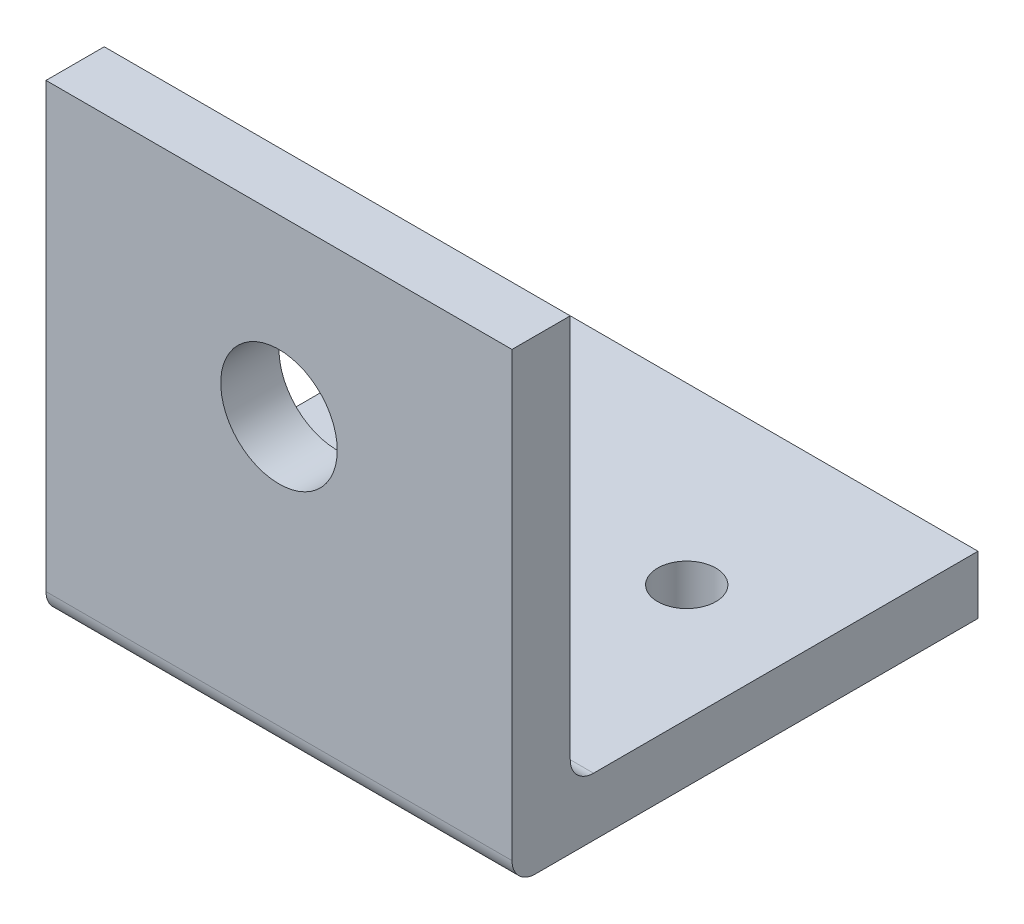
SolidWorks part; units mm, degrees
ref_plane "Ön Düzlem" through (0, 0, 0) normal (0, 0, 1) x (1, 0, 0)
ref_plane "Üst Düzlem" through (0, 0, 0) normal (0, 1, 0) x (1, 0, 0)
ref_plane "Sağ Düzlem" through (0, 0, 0) normal (1, 0, 0) x (0, 0, -1)
sketch "Çizim1" plane through (0, 0, 0) normal (1, 0, 0) x (0, 0, -1)
  line L0 (-17.8957, 38.6433) -> (-17.8957, 0.6433)
  line L1 (-15.8957, -1.3567) -> (22.1043, -1.3567)
  line L2 (-12.8957, 38.6433) -> (-12.8957, 3.6433)
  line L3 (-12.8957, 3.6433) -> (22.1043, 3.6433)
  line L4 (-17.8957, 38.6433) -> (-12.8957, 38.6433)
  line L5 (22.1043, -1.3567) -> (22.1043, 3.6433)
  arc A0 (-17.8957, 0.6433) -> (-15.8957, -1.3567) centre (-15.8957, 0.6433) ccw
  arc A1 (-12.8957, 3.6433) -> (-12.8957, 3.6433) centre (-12.8957, 3.6433) ccw
  dimension "D1" = 2
  dimension "D2" = 38
  dimension "D3" = 38
  dimension "D4" = 5
extrude "Yükseklik-Ekstrüzyon1" add sketch "Çizim1" along normal blind 40
fillet "Radyus1" radius 2 1 edges at (20, 3.6433, 12.8957)
sketch "Çizim2" plane through (0, 0, 17.8957) normal (0, 0, 1) x (1, 0, 0)
  line L0 (40, 38.6433) -> (40, 0.6433) construction
  line L1 (40, 38.6433) -> (0, 38.6433) construction
  circle A0 centre (20, 23.6433) radius 5
  dimension "D1" = 10
  dimension "D2" = 20
  dimension "D3" = 15
extrude "Kes-Ekstrüzyon1" cut sketch "Çizim2" against normal through all
sketch "Çizim3" plane through (0, 3.6433, 0) normal (0, 1, 0) x (1, 0, 0)
  line L0 (0, 22.1043) -> (0, -10.8957) construction
  line L2 (40, 22.1043) -> (0, 22.1043) construction
  circle A0 centre (10, 7.1043) radius 2.5
  circle A1 centre (30, 7.1043) radius 2.5
  point P6 (0, 0)
  dimension "D1" = 5
  dimension "D2" = 5
  dimension "D3" = 10
  dimension "D4" = 20
  dimension "D5" = 15
  dimension "D6" = 15
extrude "Kes-Ekstrüzyon2" cut sketch "Çizim3" against normal through all
